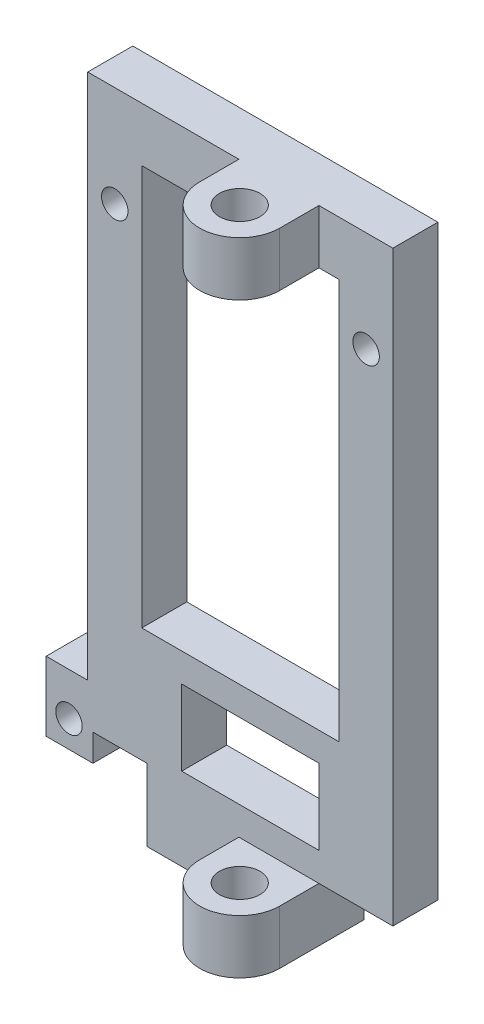
SolidWorks part; units mm, degrees
ref_plane "Front Plane" through (0, 0, 0) normal (0, 0, 1) x (1, 0, 0)
ref_plane "Top Plane" through (0, 0, 0) normal (0, 1, 0) x (1, 0, 0)
ref_plane "Right Plane" through (0, 0, 0) normal (1, 0, 0) x (0, 0, -1)
sketch "Sketch2" plane through (0, 0, 0) normal (0, 0, 1) x (1, 0, 0)
  line L1 (-21.65, 35.595) -> (21.65, 35.595)
  line L2 (-21.65, 35.595) -> (-21.65, -35.595)
  line L3 (-21.65, -35.595) -> (21.65, -35.595)
  line L4 (21.65, 35.595) -> (21.65, -35.595)
  line L5 (-15.65, 29.595) -> (15.65, 29.595)
  line L6 (-15.65, 29.595) -> (-15.65, -29.595)
  line L7 (-15.65, -29.595) -> (15.65, -29.595)
  line L8 (15.65, 29.595) -> (15.65, -29.595)
  dimension "D1" = 71.19
  dimension "D2" = 43.3
  dimension "D3" = 35.595
  dimension "D4" = 21.65
  dimension "D5" = 6
  dimension "D6" = 6
  dimension "D7" = 6
  dimension "D8" = 6
extrude "Boss-Extrude1" add sketch "Sketch2" along normal blind 5
sketch "Sketch3" plane through (0, 0, 5) normal (0, 0, 1) x (1, 0, 0)
  line L0 (0, 35.595) -> (0, -35.595)
  line L1 (21.65, 35.595) -> (-21.65, 35.595) construction
  line L2 (-21.65, -35.595) -> (21.65, -35.595) construction
  line L3 (15.65, 29.595) -> (-15.65, 29.595) construction
  line L4 (-4.445, 35.595) -> (4.445, 35.595)
  line L5 (-4.445, 35.595) -> (-4.445, 29.595)
  line L6 (-4.445, 29.595) -> (4.445, 29.595)
  line L7 (4.445, 35.595) -> (4.445, 29.595)
  line L8 (-15.65, -29.595) -> (15.65, -29.595) construction
  line L9 (-4.445, -29.595) -> (4.445, -29.595)
  line L10 (-4.445, -29.595) -> (-4.445, -35.595)
  line L11 (-4.445, -35.595) -> (4.445, -35.595)
  line L12 (4.445, -29.595) -> (4.445, -35.595)
  point P18 (4.445, -32.595)
  dimension "D1" = 8.89
  dimension "D2" = 4.445
  dimension "D3" = 8.89
extrude "Boss-Extrude2" add sketch "Sketch3" along normal blind 8.8 contours L4 L7 L6 L5 | L9 L12 L11 L10
sketch "Sketch5" plane through (0, 35.595, 0) normal (0, 1, 0) x (1, 0, 0)
  line L0 (4.445, -13.8) -> (4.445, -5) construction
  line L1 (-4.445, -13.8) -> (-4.445, -5) construction
  arc A0 (4.445, -9.4) -> (-4.445, -9.4) centre (0, -9.3548) cw
  circle A1 centre (0, -9.3548) radius 2.2479
  line M5 (-4.445, -5) -> (-4.445, -13.8)
  line M6 (-4.445, -13.8) -> (4.445, -13.8)
  line M7 (4.445, -13.8) -> (4.445, -5)
extrude "Cut-Extrude1" cut sketch "Sketch5" against normal through all and the other way through all contours A0 M6 M5 | A0 M7 M6 | A1
sketch "Sketch8" plane through (0, 0, 5) normal (0, 0, 1) x (1, 0, 0)
  line L1 (4.445, 29.595) -> (15.65, 29.595)
  line L2 (4.445, 29.595) -> (4.445, -29.595)
  line L3 (4.445, -29.595) -> (15.65, -29.595)
  line L4 (15.65, 29.595) -> (15.65, -29.595)
extrude "Boss-Extrude4" add sketch "Sketch8" against normal blind 5
sketch "Sketch9" plane through (0, 0, 5) normal (0, 0, 1) x (1, 0, 0)
  line L0 (4.445, -35.595) -> (21.65, -35.595) construction
  line L1 (21.65, 35.595) -> (12.65, 35.595)
  line L2 (21.65, 35.595) -> (21.65, -35.595)
  line L3 (21.65, -35.595) -> (12.65, -35.595)
  line L4 (12.65, 35.595) -> (12.65, -35.595)
  line L6 (6.655, -29.595) -> (4.445, -29.595)
  line L7 (6.655, -29.595) -> (6.655, 29.595)
  line L8 (6.655, 29.595) -> (4.445, 29.595)
  line L9 (4.445, -29.595) -> (4.445, 29.595)
  dimension "D1" = 9
  dimension "D2" = 2.21
extrude "Cut-Extrude2" cut sketch "Sketch9" against normal blind 5
sketch "Sketch10" plane through (0, 0, 5) normal (0, 0, 1) x (1, 0, 0)
  line L0 (-15.65, -29.595) -> (-4.445, -29.595) construction
  line L1 (-15.65, 29.595) -> (-15.23, 29.595)
  line L2 (-15.65, 29.595) -> (-15.65, -29.595)
  line L3 (-15.65, -29.595) -> (-15.23, -29.595)
  line L4 (-15.23, 29.595) -> (-15.23, -29.595)
  dimension "D1" = 0.42
extrude "Boss-Extrude5" add sketch "Sketch10" against normal blind 5
sketch "Sketch11" plane through (0, 0, 5) normal (0, 0, 1) x (1, 0, 0)
  line L0 (-21.65, -35.595) -> (-4.445, -35.595) construction
  line L1 (-21.65, 35.595) -> (-21.23, 35.595)
  line L2 (-21.65, 35.595) -> (-21.65, -35.595)
  line L3 (-21.65, -35.595) -> (-21.23, -35.595)
  line L4 (-21.23, 35.595) -> (-21.23, -35.595)
  dimension "D1" = 0.42
extrude "Cut-Extrude3" cut sketch "Sketch11" against normal blind 5
sketch "Sketch12" plane through (0, 0, 5) normal (0, 0, 1) x (1, 0, 0)
  line L1 (6.655, -29.595) -> (0, -29.595)
  line L2 (6.655, -29.595) -> (6.655, -18.927)
  line L3 (6.655, -18.927) -> (0, -18.927)
  line L4 (0, -29.595) -> (0, -18.927)
  dimension "D1" = 10.668
extrude "Boss-Extrude6" add sketch "Sketch12" against normal blind 5
sketch "Sketch13" plane through (0, 0, 5) normal (0, 0, 1) x (1, 0, 0)
  line L0 (12.65, 35.595) -> (12.65, -35.595) construction
  line L5 (4.445, -35.595) -> (12.65, -35.595)
  line L6 (4.445, -35.595) -> (4.445, -29.595)
  line L7 (4.445, -29.595) -> (12.65, -29.595)
  line L8 (12.65, -35.595) -> (12.65, -29.595)
  dimension "D1" = 6
extrude "Cut-Extrude4" cut sketch "Sketch13" against normal blind 5
sketch "Sketch14" plane through (0, 0, 5) normal (0, 0, 1) x (1, 0, 0)
  line L0 (0, -29.595) -> (4.445, -29.595) construction
  line L1 (0, -18.927) -> (2, -18.927)
  line L2 (0, -18.927) -> (0, -29.595)
  line L3 (0, -29.595) -> (2, -29.595)
  line L4 (2, -18.927) -> (2, -29.595)
  dimension "D1" = 2
extrude "Cut-Extrude5" cut sketch "Sketch14" against normal blind 5
sketch "Sketch15" plane through (-21.23, 0, 0) normal (-1, 0, 0) x (0, 0, 1)
  line L0 (5, -35.595) -> (5, 35.595) construction
  line L1 (0, -35.595) -> (5, -35.595)
  line L2 (0, -35.595) -> (0, -22.895)
  line L3 (0, -22.895) -> (5, -22.895)
  line L4 (5, -35.595) -> (5, -22.895)
  dimension "D1" = 12.7
extrude "Boss-Extrude7" add sketch "Sketch15" along normal blind 4.62
sketch "Sketch16" plane through (0, 0, 5) normal (0, 0, 1) x (1, 0, 0)
  line L0 (-15.23, -29.595) -> (-15.23, 29.595) construction
  line L5 (-4.445, -29.595) -> (-15.23, -29.595)
  line L6 (-4.445, -29.595) -> (-4.445, -18.927)
  line L7 (-4.445, -18.927) -> (-15.23, -18.927)
  line L8 (-15.23, -29.595) -> (-15.23, -18.927)
  dimension "D1" = 10.668
extrude "Boss-Extrude8" add sketch "Sketch16" against normal blind 5
sketch "Sketch17" plane through (0, 0, 5) normal (0, 0, 1) x (1, 0, 0)
  line L1 (-25.85, -35.595) -> (-14.65, -35.595)
  line L2 (-25.85, -35.595) -> (-25.85, -30.595)
  line L3 (-25.85, -30.595) -> (-14.65, -30.595)
  line L4 (-14.65, -35.595) -> (-14.65, -30.595)
  line L5 (-14.65, -30.595) -> (-20.65, -30.595)
  line L6 (-14.65, -30.595) -> (-14.65, -27.595)
  line L7 (-14.65, -27.595) -> (-20.65, -27.595)
  line L8 (-20.65, -30.595) -> (-20.65, -27.595)
  line M14 (-25.85, -22.895) -> (-25.85, -35.595)
  line M15 (-25.85, -35.595) -> (-4.445, -35.595)
  dimension "D1" = 11.2
  dimension "D2" = 5
  dimension "D3" = 6
  dimension "D4" = 3
extrude "Cut-Extrude6" cut sketch "Sketch17" against normal blind 5 contours L8 L3 L6 L7 | L4 L3 M15 M14
sketch "Sketch18" plane through (0, 0, 5) normal (0, 0, 1) x (1, 0, 0)
  line L0 (-25.85, -30.595) -> (-25.85, -22.895) construction
  line L1 (-25.85, -30.595) -> (-20.65, -30.595) construction
  circle A0 centre (-23.31, -27.625) radius 1.47
  dimension "D1" = 2.54
  dimension "D2" = 2.97
extrude "Cut-Extrude7" cut sketch "Sketch18" against normal blind 5
sketch "Sketch23" plane through (0, 0, 5) normal (0, 0, 1) x (1, 0, 0)
  line L0 (-4.445, 35.595) -> (-21.23, 35.595) construction
  line L1 (-21.23, -22.895) -> (-21.23, 35.595) construction
  line L2 (12.65, 35.595) -> (12.65, -29.595) construction
  line L3 (12.65, 35.595) -> (4.445, 35.595) construction
  circle A0 centre (-18.23, 24.405) radius 1.47
  circle A1 centre (9.68, 24.405) radius 1.47
  dimension "D1" = 11.19
  dimension "D3" = 2.97
  dimension "D2" = 3
  dimension "D4" = 11.19
extrude "Cut-Extrude10" cut sketch "Sketch23" against normal blind 5
sketch "Sketch25" plane through (0, 0, 5) normal (0, 0, 1) x (1, 0, 0)
  line L0 (6.655, -18.927) -> (6.655, 29.595) construction
  line L1 (6.655, -8.7964) -> (-15.6357, -8.7964)
  line L2 (6.655, -8.7964) -> (6.655, -27.0114)
  line L3 (6.655, -27.0114) -> (-15.6357, -27.0114)
  line L4 (-15.6357, -8.7964) -> (-15.6357, -27.0114)
  line L6 (2, -29.595) -> (-4.4903, -29.595)
  line L7 (2, -29.595) -> (2, -27.0114)
  line L8 (2, -27.0114) -> (-4.4903, -27.0114)
  line L9 (-4.4903, -29.595) -> (-4.4903, -27.0114)
  line M6 (-4.445, -29.595) -> (-4.445, -18.927)
  line M7 (-4.445, -18.927) -> (-15.23, -18.927)
  line M8 (-15.23, -18.927) -> (-15.23, 29.595)
extrude "Boss-Extrude12" add sketch "Sketch25" against normal blind 5 contours L3 L2 L1 M8 M7 M6 | L6 L7 L3 M6
sketch "Sketch26" plane through (0, 0, 5) normal (0, 0, 1) x (1, 0, 0)
  line L0 (4.445, -29.595) -> (4.445, -8.7964)
  line L1 (6.655, -8.7964) -> (-15.23, -8.7964) construction
  line L2 (4.445, -29.595) -> (4.445, -26.42)
  line L3 (6.655, -8.7964) -> (6.655, 29.595) construction
  line L4 (4.445, -26.42) -> (-10.795, -26.42)
  line L5 (4.445, -26.42) -> (4.445, -18.038)
  line L6 (4.445, -18.038) -> (-10.795, -18.038)
  line L7 (-10.795, -26.42) -> (-10.795, -18.038)
  line L8 (-15.23, -8.7964) -> (6.655, -8.7964)
  line L9 (-15.23, -8.7964) -> (-15.23, -14.863)
  line L10 (-15.23, -14.863) -> (6.655, -14.863)
  line L11 (6.655, -8.7964) -> (6.655, -14.863)
  line M6 (6.655, -8.7964) -> (-15.23, -8.7964)
  dimension "D1" = 3.175
  dimension "D2" = 15.24
  dimension "D3" = 8.382
  dimension "D4" = 0
  dimension "D5" = 3.175
extrude "Cut-Extrude11" cut sketch "Sketch26" against normal blind 5 contours L7 L4 L0 L6 | L9 L10 L0 M6 | L11 L0 L10 M6
